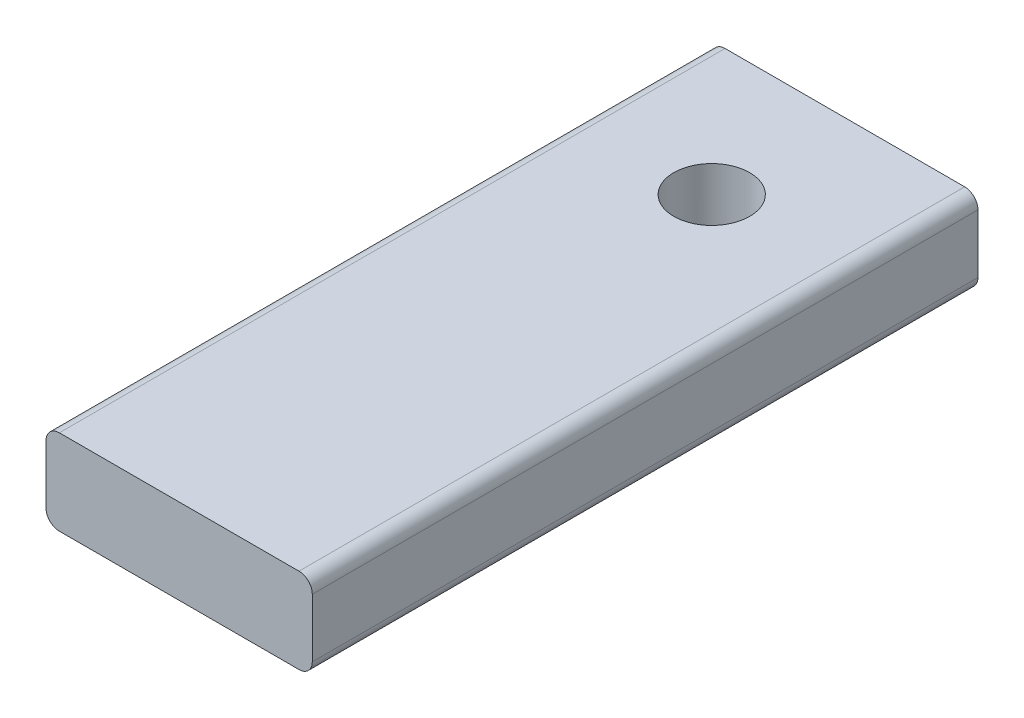
SolidWorks part; units mm, degrees
ref_plane "Front Plane" through (0, 0, 0) normal (0, 0, 1) x (1, 0, 0)
ref_plane "Top Plane" through (0, 0, 0) normal (0, 1, 0) x (1, 0, 0)
ref_plane "Right Plane" through (0, 0, 0) normal (1, 0, 0) x (0, 0, -1)
sketch "Sketch1" plane through (0, 0, 0) normal (0, 0, 1) x (1, 0, 0)
  line L0 (-9, -3.2) -> (9, -3.2)
  line L1 (10, -2.2) -> (10, 2.2)
  line L2 (9, 3.2) -> (-9, 3.2)
  line L3 (-10, 2.2) -> (-10, -2.2)
  arc A0 (9, -3.2) -> (10, -2.2) centre (9, -2.2) ccw
  arc A1 (10, 2.2) -> (9, 3.2) centre (9, 2.2) ccw
  arc A2 (-9, 3.2) -> (-10, 2.2) centre (-9, 2.2) ccw
  arc A3 (-10, -2.2) -> (-9, -3.2) centre (-9, -2.2) ccw
extrude "Boss-Extrude1" add sketch "Sketch1" along normal blind 50
ref_plane "Plane1" through (0, -4, 0) normal (0, 1, 0) x (1, 0, 0)
sketch "Sketch2" plane through (0, -4, 0) normal (0, 1, 0) x (1, 0, 0)
  circle A0 centre (0, -10) radius 2.85
extrude "Cut-Extrude1" cut sketch "Sketch2" along normal blind 8
